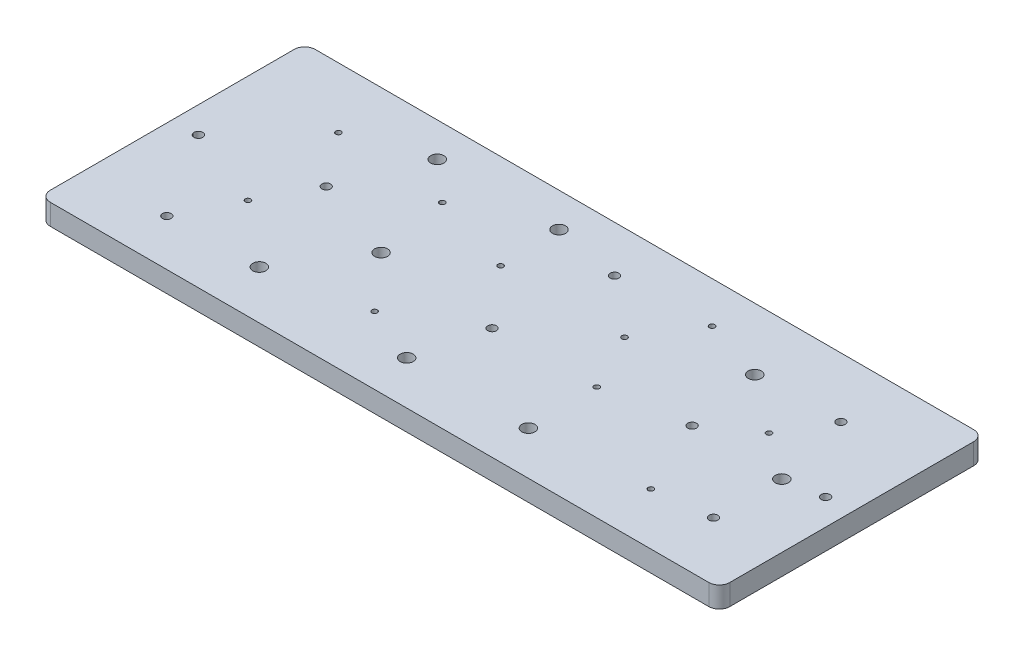
SolidWorks part; units mm, degrees
material "1060 Alloy"
ref_plane "Front Plane" through (0, 0, 0) normal (0, 0, 1) x (1, 0, 0)
ref_plane "Top Plane" through (0, 0, 0) normal (0, 1, 0) x (1, 0, 0)
ref_plane "Right Plane" through (0, 0, 0) normal (1, 0, 0) x (0, 0, -1)
sketch "Sketch1" plane through (0, 0, 0) normal (0, 1, 0) x (1, 0, 0)
  line L1 (0, 0) -> (650, 0)
  line L2 (0, 0) -> (0, 253.35)
  line L3 (0, 253.35) -> (650, 253.35)
  line L4 (650, 0) -> (650, 253.35)
  dimension "D1" = 253.35
  dimension "D2" = 650
extrude "Boss-Extrude1" add sketch "Sketch1" along normal blind 20 contours L2 L3 L4 L1
fillet "Fillet1" radius 10 4 edges at (0, 10, 0) (650, 10, 0) (650, 10, -253.35) (0, 10, -253.35)
sketch "Sketch4" plane through (0, 20, 0) normal (0, 1, 0) x (1, 0, 0)
  point P0 (90.0583, 195.4825)
  point P2 (255.539, 64.7324)
  point P4 (396.504, 162.795)
  point P6 (544.9599, 152.5801)
  point P8 (534.745, 49.7506)
  point P10 (278.0117, 162.795)
  point P12 (102.9971, 96.0579)
  point P14 (429.1915, 213.8692)
  point P16 (424.4246, 108.3157)
  point P18 (197.6548, 187.3106)
hole_wizard "Ø5.2 (5.2) Diameter Hole1" positions "Sketch4" profile "Sketch3" hole size "Ø5.2" standard "DIN" end condition through all
sketch "Sketch3" plane through (90.0583, 20, -195.4825) normal (1, 0, 0) x (0, 0, 1)
  line L0 (0, 0) -> (0, 20)
  line L1 (0, 20) -> (2.6, 20)
  line L2 (2.6, 20) -> (2.6, 0)
  line L5 (2.6, 0) -> (0, 0)
  line L11 (0, -6.35) -> (0, 107.95) construction
  dimension "Thru Hole Dia." = 5.2
  dimension "Thru Hole Depth" = 20
sketch "Sketch7" plane through (0, 20, 0) normal (0, 1, 0) x (1, 0, 0)
  point P0 (128.8748, 145.0892)
  point P4 (77.1195, 44.3026)
  point P6 (325.681, 106.9538)
  point P8 (340.6628, 209.1023)
  point P10 (502.0575, 121.9355)
  point P12 (570.1565, 196.1635)
  point P14 (588.5433, 55.8795)
hole_wizard "Ø8.3 (8.3) Diameter Hole1" positions "Sketch7" profile "Sketch6" hole size "Ø8.3" standard "DIN" end condition through all
sketch "Sketch6" plane through (128.8748, 20, -145.0892) normal (1, 0, 0) x (0, 0, 1)
  line L0 (0, 0) -> (0, 20)
  line L1 (0, 20) -> (4.15, 20)
  line L2 (4.15, 20) -> (4.15, 0)
  line L5 (4.15, 0) -> (0, 0)
  line L11 (0, -6.35) -> (0, 107.95) construction
  dimension "Thru Hole Dia." = 8.3
  dimension "Thru Hole Depth" = 20
sketch "Sketch10" plane through (0, 20, 0) normal (0, 1, 0) x (1, 0, 0)
  point P0 (209.9126, 116.4876)
  point P2 (425.7866, 41.5787)
  point P4 (489.7997, 194.1205)
  point P6 (309.3372, 41.5787)
  point P8 (163.6053, 46.3456)
  point P10 (159.5193, 220.6791)
  point P12 (275.9687, 220.6791)
  point P14 (589.2243, 120.5736)
hole_wizard "Ø12.5 (12.5) Diameter Hole1" positions "Sketch10" profile "Sketch9" hole size "Ø12.5" standard "DIN" end condition through all
sketch "Sketch9" plane through (209.9126, 20, -116.4876) normal (1, 0, 0) x (0, 0, 1)
  line L0 (0, 0) -> (0, 20)
  line L1 (0, 20) -> (6.25, 20)
  line L2 (6.25, 20) -> (6.25, 0)
  line L5 (6.25, 0) -> (0, 0)
  line L11 (0, -6.35) -> (0, 107.95) construction
  dimension "Thru Hole Dia." = 12.5
  dimension "Thru Hole Depth" = 20
sketch "Sketch11" plane through (0, 20, 0) normal (0, 1, 0) x (1, 0, 0)
  line L0 (50, 253.35) -> (50, 0) construction
  line L1 (10, 253.35) -> (640, 253.35) construction
  line L2 (10, 0) -> (640, 0) construction
  line L3 (50, 126.675) -> (0, 126.675) construction
  line L4 (0, 10) -> (0, 243.35) construction
  line L5 (600, 253.35) -> (600, 0) construction
  line L6 (600, 126.675) -> (650, 126.675) construction
  line L7 (650, 10) -> (650, 243.35) construction
  point P17 (625, 126.675)
  point P19 (25, 126.675)
  dimension "D1" = 50
  dimension "D2" = 50
hole_wizard "M8 Clearance Hole1" positions "Sketch11" profile "Sketch12" hole size "M8" standard "DIN"
sketch "Sketch12" plane through (25, 20, -126.675) normal (1, 0, 0) x (0, 0, 1)
  line L0 (0, 0) -> (0, 32.5236)
  line L1 (0, 32.5236) -> (4.2, 30)
  line L2 (4.2, 30) -> (4.2, 0)
  line L5 (4.2, 0) -> (0, 0)
  line L10 (0, 32.5236) -> (-4.2, 30) construction
  line L11 (0, -6.35) -> (0, 107.95) construction
  dimension "Hole Dia." = 8.4
  dimension "Hole Depth" = 30
  dimension "Drill Angle" = 118
sketch "Sketch13" plane through (0, 0, 0) normal (0, -1, 0) x (-1, 0, 0)
  line L0 (-30, 0) -> (-30, 253.35) construction
  line L1 (-10, 0) -> (-640, 0) construction
  line L2 (-10, 253.35) -> (-640, 253.35) construction
  line L3 (-620, 0) -> (-620, 253.35) construction
  line L4 (-30, 60) -> (0, 60) construction
  line L5 (0, 10) -> (0, 243.35) construction
  line L6 (-30, 193.35) -> (0, 193.35) construction
  line L7 (-620, 60) -> (-650, 60) construction
  line L8 (-650, 10) -> (-650, 243.35) construction
  line L9 (-620, 193.35) -> (-650, 193.35) construction
  circle A0 centre (-15, 60) radius 2
  circle A1 centre (-15, 193.35) radius 2
  circle A2 centre (-635, 60) radius 2
  circle A3 centre (-635, 193.35) radius 2
  dimension "D1" = 30
  dimension "D2" = 30
  dimension "D3" = 60
  dimension "D4" = 60
  dimension "D5" = 60
extrude "Cut-Extrude1" [suppressed] cut sketch "Sketch13" against normal through all
